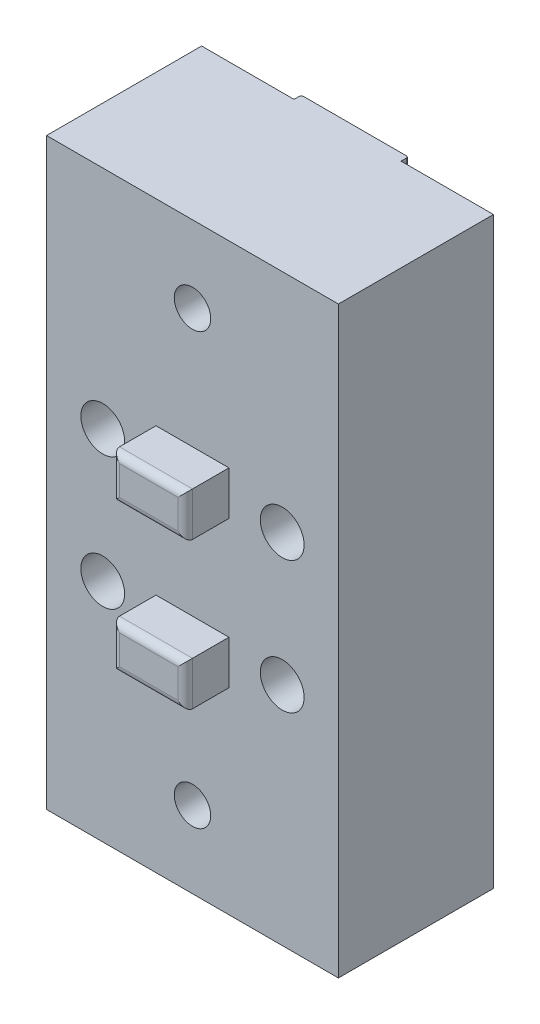
SolidWorks part; units mm, degrees
ref_plane "Front Plane" through (0, 0, 0) normal (0, 0, 1) x (1, 0, 0)
ref_plane "Top Plane" through (0, 0, 0) normal (0, 1, 0) x (1, 0, 0)
ref_plane "Right Plane" through (0, 0, 0) normal (1, 0, 0) x (0, 0, -1)
sketch "Sketch1" plane through (0, 0, 0) normal (0, 0, 1) x (1, 0, 0)
  line L0 (-12.3, 9.05) -> (12.3, 9.05) construction
  line L1 (12.3, 9.05) -> (12.3, -9.05) construction
  line L2 (12.3, -9.05) -> (-12.3, -9.05) construction
  line L3 (-12.3, -9.05) -> (-12.3, 9.05) construction
  line L4 (-12.3, 9.05) -> (-12.3, 0) construction
  line L5 (-12.3, 0) -> (12.3, 0) construction
  line L6 (-12.3, 9.05) -> (0, 9.05) construction
  line L7 (0, 9.05) -> (0, -9.05) construction
  line L13 (0, 0) -> (-20, 0) construction
  line L14 (0, 0) -> (20, 0) construction
  line L16 (0, 0) -> (0, 40) construction
  line L17 (0, 9.05) -> (0, -30.95) construction
  line L18 (0, 0) -> (0, -40) construction
  line L20 (-20, 40) -> (20, 40)
  line L21 (-20, 40) -> (-20, -40)
  line L22 (-20, -40) -> (20, -40)
  line L23 (20, 40) -> (20, -40)
  circle A0 centre (12.3, 9.05) radius 2
  circle A1 centre (12.3, -9.05) radius 2
  circle A2 centre (-12.3, 9.05) radius 2
  circle A3 centre (-12.3, -9.05) radius 2
  point P10 (0, 0)
  dimension "D1" = 4
  dimension "D2" = 4
  dimension "D3" = 4
  dimension "D4" = 4
  dimension "D5" = 20
  dimension "D6" = 20
  dimension "D7" = 40
  dimension "D8" = 40
extrude "Boss-Extrude1" add sketch "Sketch1" along normal blind 21.25
sketch "Sketch2" plane through (0, 0, 21.25) normal (0, 0, 1) x (1, 0, 0)
  line L0 (0, 40) -> (0, -40) construction
  line L1 (-20, 0) -> (20, 0) construction
  line L2 (0, 0) -> (-13.05, 0) construction
  line L3 (-13.05, 0) -> (-10.05, 0) construction
  line L9 (-10.05, -5) -> (-10.05, 5) construction
  line L10 (-13.0279, 0) -> (-7.0721, 0) construction
  line L14 (0, 0) -> (0, -13.05) construction
  line L15 (0, -13.05) -> (0, -10.05) construction
  line L16 (0, -13.05) -> (5, -13.05)
  line L17 (0, -13.05) -> (-5, -13.05) construction
  line L18 (-5, -13.05) -> (-5, -7.05) construction
  line L19 (-5, -7.05) -> (5, -7.05) construction
  line L20 (5, -7.05) -> (5, -13.05) construction
  line L21 (5, 7.05) -> (5, 13.05)
  line L22 (-5, -7.05) -> (5, -7.05)
  line L23 (-5, -7.05) -> (-5, -13.05)
  line L24 (-5, -13.05) -> (5, -13.05)
  line L25 (5, -7.05) -> (5, -13.05)
  line L26 (-5, 7.05) -> (5, 7.05)
  line L27 (-5, 7.05) -> (-5, 13.05)
  line L28 (-5, 13.05) -> (5, 13.05)
  dimension "D1" = 13.05
  dimension "D2" = 3
  dimension "D3" = 5
  dimension "D4" = 5
  dimension "D5" = 13.05
  dimension "D6" = 3
  dimension "D7" = 6
sketch "Sketch4" plane through (0, 0, 0) normal (0, 0, -1) x (-1, 0, 0)
  line L0 (0, 40) -> (0, -40) construction
  line L1 (-20, 0) -> (20, 0) construction
  line L2 (0, 0) -> (-7.335, 0) construction
  line L3 (0, 0) -> (7.335, 0) construction
  line L4 (-7.335, 40) -> (-7.335, -40)
  line L5 (7.335, -40) -> (7.335, 40)
  line L6 (7.335, 40) -> (-7.335, 40)
  line L7 (-7.335, -40) -> (7.335, -40)
  dimension "D1" = 7.335
  dimension "D2" = 7.335
extrude "Boss-Extrude3" add sketch "Sketch4" along normal blind 1
fillet "Fillet1" radius 0.25 1 edges at (7.335, 0, -1)
fillet "Fillet2" radius 0.25 1 edges at (-7.335, 0, -1)
extrude "Boss-Extrude4" add sketch "Sketch2" along normal blind 6 contours L25 L22 L23 L24 L16 | L28 L27 L26 L21
sketch "Sketch5" plane through (0, 0, -1) normal (0, 0, -1) x (-1, 0, 0)
  line L0 (-7.085, 0) -> (7.085, 0) construction
  line L1 (0, 40) -> (0, -40) construction
  line L2 (0, 0) -> (0, 32.5) construction
  line L3 (0, 0) -> (0, 26.5) construction
  line L4 (0, 26.5) -> (0, 29.5) construction
  circle A0 centre (0, 29.5) radius 2.5
  circle A1 centre (0, -29.5) radius 2.5
  dimension "D4" = 5
  dimension "D1" = 32.5
  dimension "D2" = 26.5
  dimension "D3" = 3
extrude "Cut-Extrude1" cut sketch "Sketch5" against normal through all
sketch "Sketch6" plane through (0, 0, 21.25) normal (0, 0, 1) x (1, 0, 0)
  circle A0 centre (-12.3, 9.05) radius 3
  circle A1 centre (12.3, 9.05) radius 3
  circle A2 centre (12.3, -9.05) radius 3
  circle A3 centre (-12.3, -9.05) radius 3
  dimension "D1" = 6
  dimension "D2" = 6
  dimension "D3" = 6
  dimension "D4" = 6
extrude "Cut-Extrude2" cut sketch "Sketch6" against normal blind 6
fillet "Fillet3" radius 1 8 edges at (5, -10.05, 27.25) (0, -13.05, 27.25) (-5, -10.05, 27.25) (0, -7.05, 27.25) (0, 7.05, 27.25) (5, 10.05, 27.25) (0, 13.05, 27.25) (-5, 10.05, 27.25)
